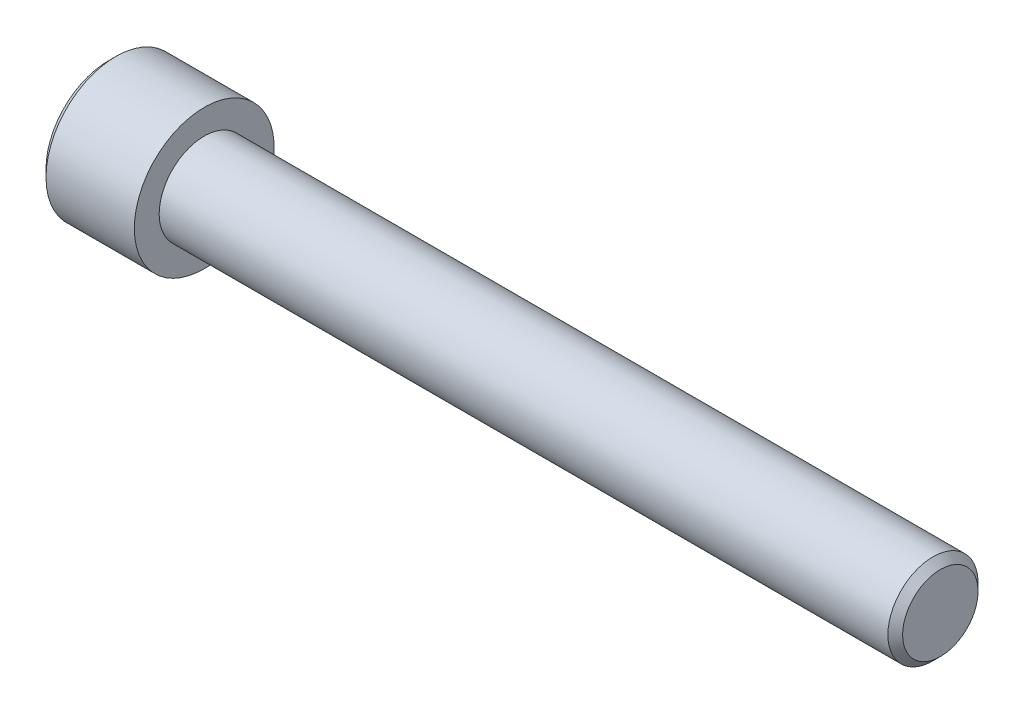
SolidWorks part; units mm, degrees
material "Galvanized Steel"
ref_plane "Front Plane" through (0, 0, 0) normal (0, 0, 1) x (1, 0, 0)
ref_plane "Top Plane" through (0, 0, 0) normal (0, 1, 0) x (1, 0, 0)
ref_plane "Right Plane" through (0, 0, 0) normal (1, 0, 0) x (0, 0, -1)
sketch "Sketch1" plane through (0, 0, 0) normal (0, 0, 1) x (1, 0, 0)
  line L0 (-40.759, 0) -> (36.5983, 0) construction
  line L1 (0, 16.757) -> (0, -12.0625) construction
  line L2 (28.702, 0) -> (28.702, 2.6035)
  line L3 (28.702, 2.6035) -> (28.194, 3.1115)
  line L4 (28.194, 3.1115) -> (-22.098, 3.1115)
  line L5 (-22.098, 3.1115) -> (-22.098, 4.826)
  line L6 (-22.098, 4.826) -> (-28.194, 4.826)
  line L7 (-28.702, 4.318) -> (-28.702, 0)
  line L8 (-28.702, 0) -> (28.702, 0)
  line L10 (-28.194, 4.826) -> (-28.702, 4.318)
  point P10 (-28.702, 4.826)
  dimension "D1" = 9.652
  dimension "D2" = 6.223
  dimension "D3" = 6.604
  dimension "D4" = 50.8
  dimension "D5" = 45
  dimension "D6" = 0.508
revolve "Revolve1" add sketch "Sketch1" angle 360 about L0
sketch "Sketch2" plane through (-28.702, 0, 0) normal (-1, 0, 0) x (0, 0, 1)
  line L0 (0, 5.0398) -> (0, -5.3552) construction
  line L1 (-5.6471, 0) -> (6.1045, 0) construction
  line L2 (0, 2.7496) -> (-2.3812, 1.3748)
  line L3 (-2.3812, 1.3748) -> (-2.3812, -1.3748)
  line L4 (-2.3812, -1.3748) -> (0, -2.7496)
  line L5 (0, -2.7496) -> (2.3812, -1.3748)
  line L6 (2.3812, -1.3748) -> (2.3812, 1.3748)
  line L7 (2.3812, 1.3748) -> (0, 2.7496)
  dimension "D1" = 5.4993
  dimension "D2" = 4.7625
  dimension "D3" = 2.7496
extrude "Extrude1" cut sketch "Sketch2" against normal blind 3.81
